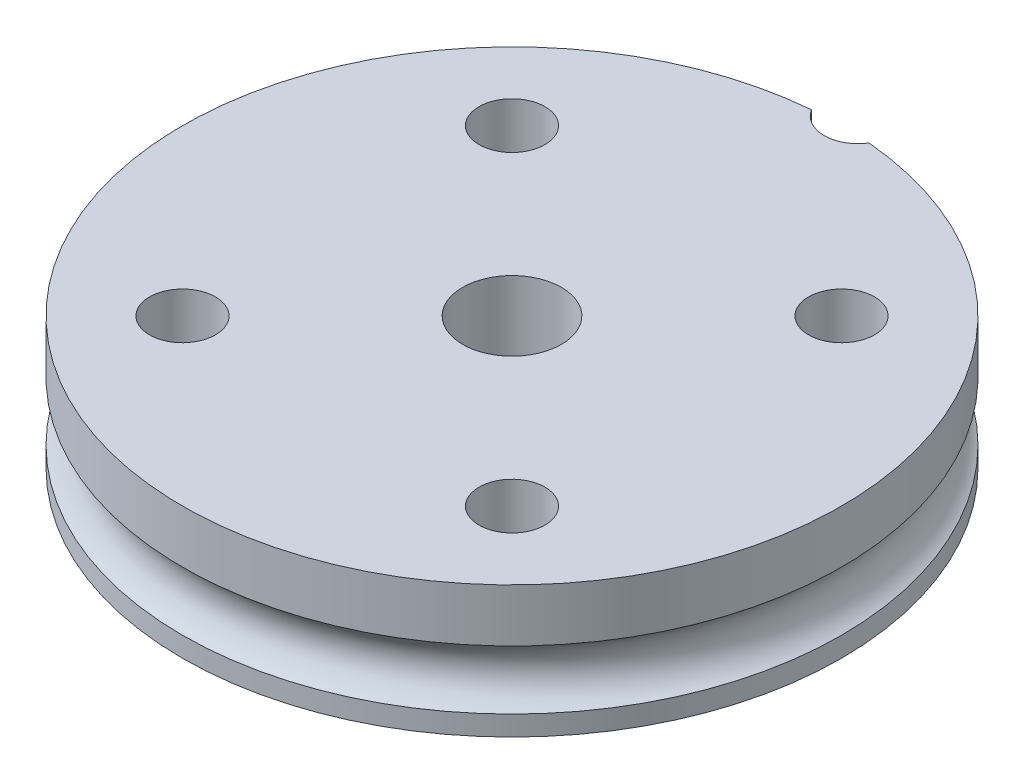
SolidWorks part; units mm, degrees
ref_plane "前视基准面" through (0, 0, 0) normal (0, 0, 1) x (1, 0, 0)
ref_plane "上视基准面" through (0, 0, 0) normal (0, 1, 0) x (1, 0, 0)
ref_plane "右视基准面" through (0, 0, 0) normal (1, 0, 0) x (0, 0, -1)
sketch "草图2" plane through (0, 0, 0) normal (0, 0, 1) x (1, 0, 0)
  line L1 (0, 0) -> (20, 0)
  line L2 (0, 0) -> (0, 8)
  line L3 (0, 8) -> (20, 8)
  line L4 (20, 0) -> (20, 8)
  line L5 (0, 8) -> (3, 8)
  line L6 (0, 8) -> (0, 0)
  line L7 (0, 0) -> (3, 0)
  line L8 (3, 8) -> (3, 0)
  circle A1 centre (21, 3) radius 2.05
  point P4 (21, 3)
  dimension "D1" = 1
  dimension "D3" = 3
  dimension "D5" = 4.1
  dimension "D2" = 8
  dimension "D4" = 20
revolve "旋转1" add sketch "草图2" angle 360 about L2
sketch "草图3" plane through (0, 0, 0) normal (0, -1, 0) x (1, 0, 0)
  line L15 (1.836, -17.3501) -> (3.4084, -10.7985)
  line L17 (-1.836, -17.3501) -> (-3.4084, -10.7985)
  line L18 (-17.3501, 1.836) -> (-10.7985, 3.4084)
  line L19 (-17.3501, -1.836) -> (-10.7985, -3.4084)
  line L20 (1.836, 17.3501) -> (3.4084, 10.7985)
  line L21 (-1.836, 17.3501) -> (-3.4084, 10.7985)
  line L22 (17.3501, -1.836) -> (10.7985, -3.4084)
  line L23 (17.3501, 1.836) -> (10.7985, 3.4084)
  line L24 (-0.5274, -18.4925) -> (0.5274, -18.4925)
  line L26 (-18.4925, 0.5274) -> (-18.4925, -0.5274)
  line L28 (-0.5274, 18.4925) -> (0.5274, 18.4925)
  line L30 (18.4925, 0.5274) -> (18.4925, -0.5274)
  arc A13 (1.836, -17.3501) -> (0.5274, -18.4925) centre (0.3774, -17) cw
  arc A14 (-0.5274, -18.4925) -> (-1.836, -17.3501) centre (-0.3774, -17) cw
  arc A15 (-17.3501, -1.836) -> (-18.4925, -0.5274) centre (-17, -0.3774) cw
  arc A16 (-18.4925, 0.5274) -> (-17.3501, 1.836) centre (-17, 0.3774) cw
  arc A17 (-1.836, 17.3501) -> (-0.5274, 18.4925) centre (-0.3774, 17) cw
  arc A18 (0.5274, 18.4925) -> (1.836, 17.3501) centre (0.3774, 17) cw
  arc A19 (17.3501, 1.836) -> (18.4925, 0.5274) centre (17, 0.3774) cw
  arc A20 (18.4925, -0.5274) -> (17.3501, -1.836) centre (17, -0.3774) cw
  arc A21 (-3.4084, -10.7985) -> (-10.7985, -3.4084) centre (-13.1322, -13.1322) ccw
  arc A22 (3.4084, -10.7985) -> (10.7985, -3.4084) centre (13.1322, -13.1322) cw
  arc A23 (3.4084, 10.7985) -> (10.7985, 3.4084) centre (13.1322, 13.1322) ccw
  arc A24 (-3.4084, 10.7985) -> (-10.7985, 3.4084) centre (-13.1322, 13.1322) cw
  circle A25 centre (0, 0) radius 3
  point P18 (0, 0)
  point P58 (0, 0)
  point P85 (0, 0)
  dimension "D1" = 10
  dimension "D2" = 4
  dimension "D5" = 1.5
  dimension "D4" = 4
extrude "切除-拉伸1" cut sketch "草图3" against normal blind 2.5
sketch "草图4" plane through (0, 0, 0) normal (0, -1, 0) x (1, 0, 0)
  line L5 (13.4852, 9.9634) -> (11.8109, 12.8634)
  line L6 (-10, -10) -> (10, -10)
  line L30 (-10, -10) -> (-10, 10)
  line L31 (-10, 10) -> (10, 10)
  line L33 (10, -10) -> (10, 10)
  line L34 (-10, -10) -> (10, 10) construction
  line L35 (-10, 10) -> (10, -10) construction
  line L36 (-10, 13.3486) -> (-12.9, 11.6743)
  line L37 (-12.9, 11.6743) -> (-12.9, 8.3257)
  line L38 (-12.9, 8.3257) -> (-10, 6.6514)
  line L39 (-10, 6.6514) -> (-7.1, 8.3257)
  line L40 (-7.1, 8.3257) -> (-7.1, 11.6743)
  line L41 (-7.1, 11.6743) -> (-10, 13.3486)
  line L42 (11.8109, 12.8634) -> (8.4623, 12.8634)
  line L43 (8.4623, 12.8634) -> (6.788, 9.9634)
  line L44 (6.788, 9.9634) -> (8.4623, 7.0634)
  line L45 (8.4623, 7.0634) -> (11.8109, 7.0634)
  line L46 (11.8109, 7.0634) -> (13.4852, 9.9634)
  line L47 (10.1, -13.5218) -> (13, -11.8475)
  line L48 (13, -11.8475) -> (13, -8.4989)
  line L49 (13, -8.4989) -> (10.1, -6.8246)
  line L50 (10.1, -6.8246) -> (7.2, -8.4989)
  line L51 (7.2, -8.4989) -> (7.2, -11.8475)
  line L52 (7.2, -11.8475) -> (10.1, -13.5218)
  line L53 (-13.3852, -10.1366) -> (-11.7109, -13.0366)
  line L54 (-11.7109, -13.0366) -> (-8.3623, -13.0366)
  line L55 (-8.3623, -13.0366) -> (-6.688, -10.1366)
  line L56 (-6.688, -10.1366) -> (-8.3623, -7.2366)
  line L57 (-8.3623, -7.2366) -> (-11.7109, -7.2366)
  line L58 (-11.7109, -7.2366) -> (-13.3852, -10.1366)
  circle A0 centre (-10, 10) radius 2.9 construction
  circle A1 centre (10.1366, 9.9634) radius 2.9 construction
  circle A2 centre (10.1, -10.1732) radius 2.9 construction
  circle A3 centre (-10.0366, -10.1366) radius 2.9 construction
  point P0 (0, 0)
  point P40 (0.05, -0.0866)
  dimension "D1" = 5.8
extrude "切除-拉伸2" cut sketch "草图4" against normal blind 3
sketch "草图6" plane through (0, 3, 0) normal (0, -1, 0) x (1, 0, 0)
  line L1 (-10, -10) -> (10, -10)
  line L2 (-10, -10) -> (-10, 10)
  line L3 (-10, 10) -> (10, 10)
  line L4 (10, -10) -> (10, 10)
  line L5 (-10, -10) -> (10, 10) construction
  line L6 (-10, 10) -> (10, -10) construction
  circle A0 centre (-10, 10) radius 2
  circle A1 centre (10, 10) radius 2
  circle A2 centre (10, -10) radius 2
  circle A3 centre (-10, -10) radius 2
  point P0 (0, 0)
  point P16 (0, 0)
extrude "切除-拉伸4" cut sketch "草图6" against normal through all contours L1 A3 L2 | L2 A3 L1 | L3 A0 L2 | L2 A0 L3 | L4 A1 L3 | L3 A1 L4 | L1 A2 L4 | L4 A2 L1
sketch "草图8" plane through (0, 8, 0) normal (0, 1, 0) x (1, 0, 0)
  circle A0 centre (0, 0) radius 20 construction
  circle A1 centre (0, 21) radius 2.05
  point P0 (0, 21)
  dimension "D1" = 21
extrude "切除-拉伸6" cut sketch "草图8" against normal blind 5 contours A1
